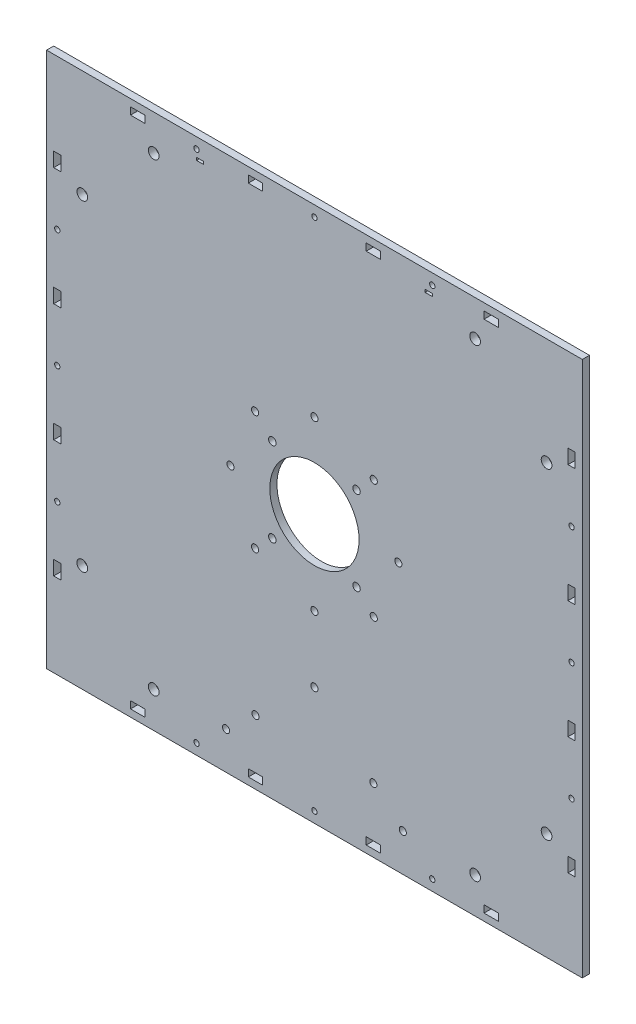
SolidWorks part; units mm, degrees
ref_plane "前视基准面" through (0, 0, 0) normal (0, 0, 1) x (1, 0, 0)
ref_plane "上视基准面" through (0, 0, 0) normal (0, 1, 0) x (1, 0, 0)
ref_plane "右视基准面" through (0, 0, 0) normal (1, 0, 0) x (0, 0, -1)
sketch "草图1" plane through (0, 0, 0) normal (0, 0, 1) x (1, 0, 0)
  line L0 (1.4571, -21.1871) -> (1.4571, -41.1871) construction
  line L1 (63.4571, 98.8129) -> (67.4571, 98.8129)
  line L2 (1.4571, -21.1871) -> (1.4571, 44.8129) construction
  line L3 (67.4571, 98.8129) -> (67.4571, 97.3129)
  line L4 (151.4571, -41.1871) -> (151.4571, 108.8129)
  line L5 (151.4571, 108.8129) -> (-148.5429, 108.8129)
  line L6 (-148.5429, 108.8129) -> (-148.5429, -191.1871)
  line L7 (-148.5429, -191.1871) -> (151.4571, -191.1871)
  line L8 (151.4571, -191.1871) -> (151.4571, -41.1871)
  line L9 (-148.5429, -41.1871) -> (-161.9412, -41.1871) construction
  line L10 (1.4571, -191.1871) -> (1.4571, -181.0361) construction
  line L11 (67.4571, 97.3129) -> (63.4571, 97.3129)
  line L12 (63.4571, 97.3129) -> (63.4571, 98.8129)
  line L13 (-64.5429, 98.8129) -> (-64.5429, 97.3129)
  line L14 (-64.5429, 97.3129) -> (-60.5429, 97.3129)
  line L15 (-60.5429, 97.3129) -> (-60.5429, 98.8129)
  line L16 (-60.5429, 98.8129) -> (-64.5429, 98.8129)
  circle A6 centre (1.4571, -21.1871) radius 241.4173 construction
  circle A9 centre (1.4571, -41.1871) radius 25
  circle A10 centre (25.0271, -17.6171) radius 2.1
  circle A11 centre (25.0271, -64.7571) radius 2.1
  circle A12 centre (-22.1129, -64.7571) radius 2.1
  circle A13 centre (-22.1129, -17.6171) radius 2.1
  dimension "D1" = 50
  dimension "D4" = 4.2
  dimension "D2" = 300
  dimension "D3" = 300
  dimension "D5" = 23.57
  dimension "D6" = 23.57
  dimension "D7" = 4
extrude "凸台-拉伸1" add sketch "草图1" along normal blind 4
sketch "草图3" plane through (0, 0, 4) normal (0, 0, 1) x (1, 0, 0)
  line L1 (96.4421, -183.1721) -> (104.4721, -183.1721)
  line L13 (1.4571, -191.1871) -> (1.4571, -185.1871) construction
  line L14 (-148.5429, -191.1871) -> (151.4571, -191.1871) construction
  line L15 (1.4571, -185.1871) -> (34.4571, -185.1871) construction
  line L16 (34.4571, -185.1871) -> (67.4571, -185.1871) construction
  line L17 (30.4421, -183.1721) -> (38.4721, -183.1721)
  line L18 (30.4421, -183.1721) -> (30.4421, -187.2021)
  line L19 (30.4421, -187.2021) -> (38.4721, -187.2021)
  line L20 (38.4721, -183.1721) -> (38.4721, -187.2021)
  line L21 (30.4421, -183.1721) -> (38.4721, -187.2021) construction
  line L22 (30.4421, -187.2021) -> (38.4721, -183.1721) construction
  line L23 (67.4571, -185.1871) -> (100.4571, -185.1871) construction
  line L24 (96.4421, -183.1721) -> (96.4421, -187.2021)
  line L25 (96.4421, -187.2021) -> (104.4721, -187.2021)
  line L26 (96.4421, -187.2021) -> (104.4721, -183.1721) construction
  line L27 (104.4721, -187.2021) -> (104.4721, -183.1721)
  line L28 (-35.5579, -183.1721) -> (-35.5579, -187.2021)
  line L29 (-27.5279, -183.1721) -> (-35.5579, -183.1721)
  line L30 (-27.5279, -183.1721) -> (-27.5279, -187.2021)
  line L31 (-27.5279, -187.2021) -> (-35.5579, -187.2021)
  line L32 (-93.5279, -183.1721) -> (-93.5279, -187.2021)
  line L33 (-101.5579, -187.2021) -> (-101.5579, -183.1721)
  line L34 (-93.5279, -183.1721) -> (-101.5579, -183.1721)
  line L35 (-93.5279, -187.2021) -> (-101.5579, -187.2021)
  line L36 (-140.5279, 53.7979) -> (-140.5279, 61.8279)
  line L37 (-144.5579, 53.7979) -> (-144.5579, 61.8279)
  line L38 (-144.5579, 61.8279) -> (-140.5279, 61.8279)
  line L39 (-140.5279, 53.7979) -> (-144.5579, 53.7979)
  line L40 (-140.5279, -12.2021) -> (-140.5279, -4.1721)
  line L41 (-140.5279, -4.1721) -> (-144.5579, -4.1721)
  line L42 (-144.5579, -12.2021) -> (-144.5579, -4.1721)
  line L43 (-140.5279, -12.2021) -> (-144.5579, -12.2021)
  line L44 (-140.5279, -70.1721) -> (-144.5579, -70.1721)
  line L45 (-140.5279, -70.1721) -> (-140.5279, -78.2021)
  line L46 (-144.5579, -70.1721) -> (-144.5579, -78.2021)
  line L47 (-140.5279, -78.2021) -> (-144.5579, -78.2021)
  line L48 (-140.5279, -136.1721) -> (-140.5279, -144.2021)
  line L49 (-144.5579, -136.1721) -> (-144.5579, -144.2021)
  line L50 (-140.5279, -136.1721) -> (-144.5579, -136.1721)
  line L51 (-144.5579, -144.2021) -> (-140.5279, -144.2021)
  line L52 (96.4421, 100.7979) -> (104.4721, 100.7979)
  line L53 (96.4421, 104.8279) -> (104.4721, 104.8279)
  line L54 (104.4721, 104.8279) -> (104.4721, 100.7979)
  line L55 (96.4421, 100.7979) -> (96.4421, 104.8279)
  line L56 (30.4421, 100.7979) -> (38.4721, 100.7979)
  line L57 (38.4721, 100.7979) -> (38.4721, 104.8279)
  line L58 (30.4421, 104.8279) -> (38.4721, 104.8279)
  line L59 (30.4421, 100.7979) -> (30.4421, 104.8279)
  line L60 (-27.5279, 100.7979) -> (-27.5279, 104.8279)
  line L61 (-27.5279, 100.7979) -> (-35.5579, 100.7979)
  line L62 (-27.5279, 104.8279) -> (-35.5579, 104.8279)
  line L63 (-35.5579, 100.7979) -> (-35.5579, 104.8279)
  line L64 (-93.5279, 100.7979) -> (-101.5579, 100.7979)
  line L65 (-93.5279, 104.8279) -> (-101.5579, 104.8279)
  line L66 (-93.5279, 100.7979) -> (-93.5279, 104.8279)
  line L67 (-101.5579, 104.8279) -> (-101.5579, 100.7979)
  line L68 (143.4421, -136.1721) -> (143.4421, -144.2021)
  line L69 (147.4721, -136.1721) -> (147.4721, -144.2021)
  line L70 (147.4721, -144.2021) -> (143.4421, -144.2021)
  line L71 (143.4421, -136.1721) -> (147.4721, -136.1721)
  line L72 (143.4421, -70.1721) -> (143.4421, -78.2021)
  line L73 (143.4421, -78.2021) -> (147.4721, -78.2021)
  line L74 (147.4721, -70.1721) -> (147.4721, -78.2021)
  line L75 (143.4421, -70.1721) -> (147.4721, -70.1721)
  line L76 (143.4421, -12.2021) -> (147.4721, -12.2021)
  line L77 (143.4421, -12.2021) -> (143.4421, -4.1721)
  line L78 (147.4721, -12.2021) -> (147.4721, -4.1721)
  line L79 (143.4421, -4.1721) -> (147.4721, -4.1721)
  line L80 (143.4421, 53.7979) -> (143.4421, 61.8279)
  line L81 (147.4721, 53.7979) -> (147.4721, 61.8279)
  line L82 (143.4421, 53.7979) -> (147.4721, 53.7979)
  line L83 (147.4721, 61.8279) -> (143.4421, 61.8279)
  line L84 (50.9571, -185.1871) -> (50.9571, -170.1871) construction
  line L85 (17.9571, -185.1871) -> (17.9571, -170.1871) construction
  line L86 (-48.0429, -170.1871) -> (-15.0429, -170.1871) construction
  line L91 (-31.5429, -170.1871) -> (-31.5429, -155.1871) construction
  circle A0 centre (1.4571, -185.1871) radius 1.5
  circle A1 centre (67.4571, -185.1871) radius 1.5
  circle A2 centre (-64.5429, -185.1871) radius 1.5
  circle A3 centre (-142.5429, 24.8129) radius 1.5
  circle A4 centre (-142.5429, -41.1871) radius 1.5
  circle A5 centre (-142.5429, -107.1871) radius 1.5
  circle A6 centre (67.4571, 102.8129) radius 1.5
  circle A7 centre (1.4571, 102.8129) radius 1.5
  circle A8 centre (-64.5429, 102.8129) radius 1.5
  circle A9 centre (145.4571, -107.1871) radius 1.5
  circle A10 centre (145.4571, -41.1871) radius 1.5
  circle A11 centre (145.4571, 24.8129) radius 1.5
  circle A15 centre (17.9571, -170.1871) radius 2 construction
  circle A16 centre (-15.0429, -170.1871) radius 2 construction
  circle A17 centre (50.9571, -170.1871) radius 2
  circle A18 centre (-48.0429, -170.1871) radius 2
  circle A19 centre (-31.5429, -155.1871) radius 2
  circle A20 centre (34.4571, -155.1871) radius 2
  circle A22 centre (1.4571, -155.1871) radius 2 construction
  circle A23 centre (1.4571, -41.1871) radius 47 construction
  circle A24 centre (1.4571, -88.1871) radius 2
  circle A25 centre (-31.7769, -74.4212) radius 2
  circle A26 centre (-45.5429, -41.1871) radius 2
  circle A27 centre (-31.7769, -7.9531) radius 2
  circle A28 centre (1.4571, 5.8129) radius 2
  circle A29 centre (34.6912, -7.9531) radius 2
  circle A30 centre (48.4571, -41.1871) radius 2
  circle A31 centre (34.6912, -74.4212) radius 2
  circle A32 centre (1.4571, -125.1871) radius 2
  dimension "D1" = 8.03
  dimension "D3" = 4
  dimension "D4" = 8
  dimension "D5" = 30
  dimension "D6" = 4
  dimension "D7" = 94
  dimension "D8" = 4
  dimension "D2" = 4.03
extrude "切除-拉伸2" cut sketch "草图3" against normal blind 4
sketch "草图6" plane through (0, 0, 4) normal (0, 0, 1) x (1, 0, 0)
sketch "草图7" plane through (0, 0, 4) normal (0, 0, 1) x (1, 0, 0)
  line L5 (-148.5429, -171.1871) -> (151.4571, -171.1871) construction
  line L6 (-148.5429, 108.8129) -> (-148.5429, -191.1871) construction
  line L7 (151.4571, -191.1871) -> (151.4571, 108.8129) construction
  line L8 (-148.5429, -191.1871) -> (151.4571, -191.1871) construction
  circle A0 centre (-88.5429, -171.1871) radius 3
  circle A1 centre (91.4571, -171.1871) radius 3
  circle A2 centre (-128.5429, 48.8129) radius 3
  circle A3 centre (-128.5429, -131.1871) radius 3
  circle A4 centre (91.4571, 88.8129) radius 3
  circle A5 centre (-88.5429, 88.8129) radius 3
  circle A6 centre (131.4571, -131.1871) radius 3
  circle A7 centre (131.4571, 48.8129) radius 3
  dimension "D2" = 6
  dimension "D4" = 60
  dimension "D1" = 20
  dimension "D3" = 60
  dimension "D5" = 4
extrude "切除-拉伸3" cut sketch "草图7" against normal blind 10
